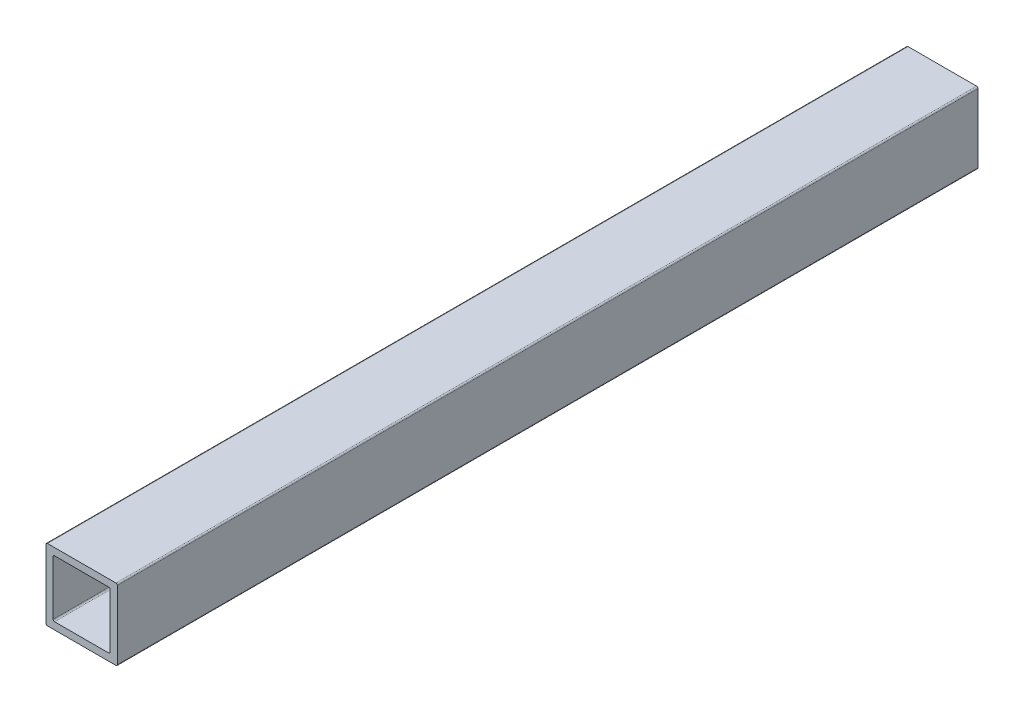
SolidWorks part; units mm, degrees
ref_plane "前基準面" through (0, 0, 0) normal (0, 0, 1) x (1, 0, 0)
ref_plane "上基準面" through (0, 0, 0) normal (0, 1, 0) x (1, 0, 0)
ref_plane "右基準面" through (0, 0, 0) normal (1, 0, 0) x (0, 0, -1)
sketch "草圖1" plane through (0, 0, 0) normal (0, 0, 1) x (1, 0, 0)
  line L1 (-5, 5) -> (5, 5)
  line L2 (-5, 5) -> (-5, -5)
  line L3 (-5, -5) -> (5, -5)
  line L4 (5, 5) -> (5, -5)
  line L5 (-4, 4) -> (4, 4)
  line L6 (-4, 4) -> (-4, -4)
  line L7 (-4, -4) -> (4, -4)
  line L8 (4, 4) -> (4, -4)
  dimension "D1" = 10
  dimension "D2" = 5
  dimension "D3" = 10
  dimension "D4" = 5
  dimension "D5" = 1
  dimension "D6" = 1
  dimension "D7" = 1
  dimension "D8" = 1
extrude "填料-伸長1" add sketch "草圖1" along normal blind 120.57
fillet "圓角1" radius 0.2 8 edges at (4, 4, 60.285) (-4, 4, 60.285) (-5, -5, 60.285) (4, -4, 60.285) (5, -5, 60.285) (-5, 5, 60.285) (-4, -4, 60.285) (5, 5, 60.285)
